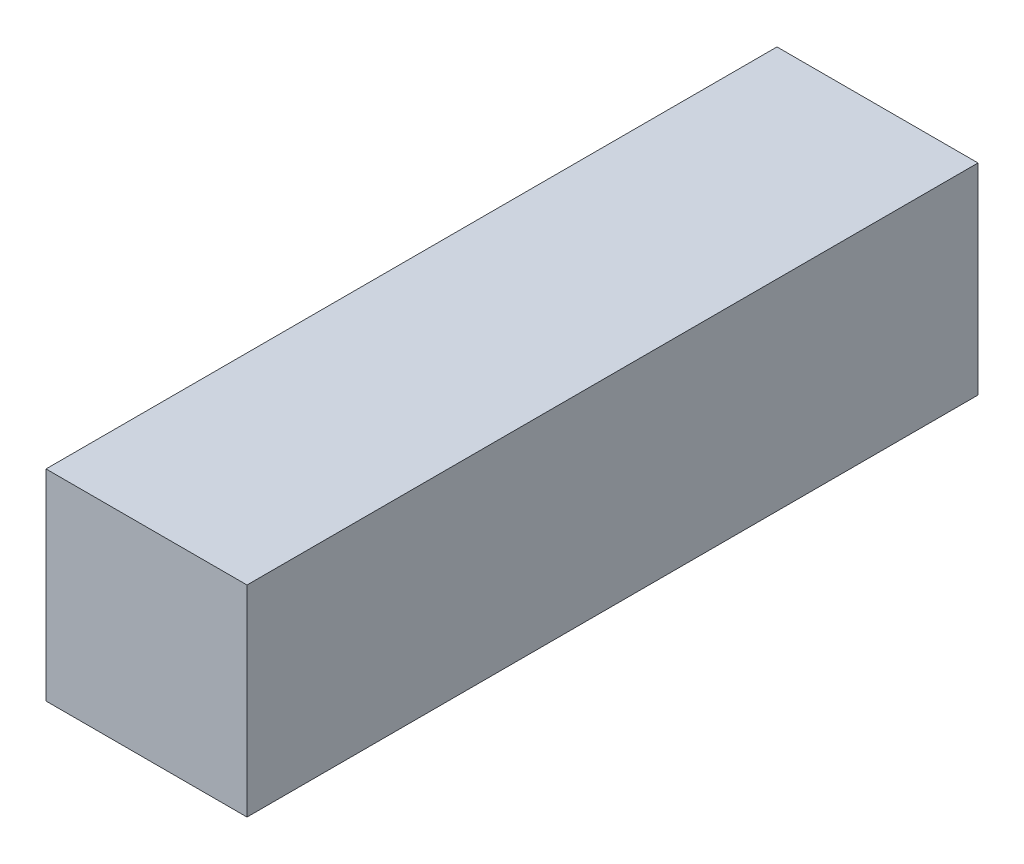
SolidWorks part; units mm, degrees
ref_plane "Plan de face" through (0, 0, 0) normal (0, 0, 1) x (1, 0, 0)
ref_plane "Plan de dessus" through (0, 0, 0) normal (0, 1, 0) x (1, 0, 0)
ref_plane "Plan de droite" through (0, 0, 0) normal (1, 0, 0) x (0, 0, -1)
sketch "Esquisse1" plane through (0, 0, 0) normal (0, 0, 1) x (1, 0, 0)
  line L1 (0, 0) -> (22, 0)
  line L2 (0, 0) -> (0, -22)
  line L3 (0, -22) -> (22, -22)
  line L4 (22, 0) -> (22, -22)
  dimension "D1" = 22
  dimension "D2" = 22
extrude "Boss.-Extru.1" add sketch "Esquisse1" along normal blind 80
